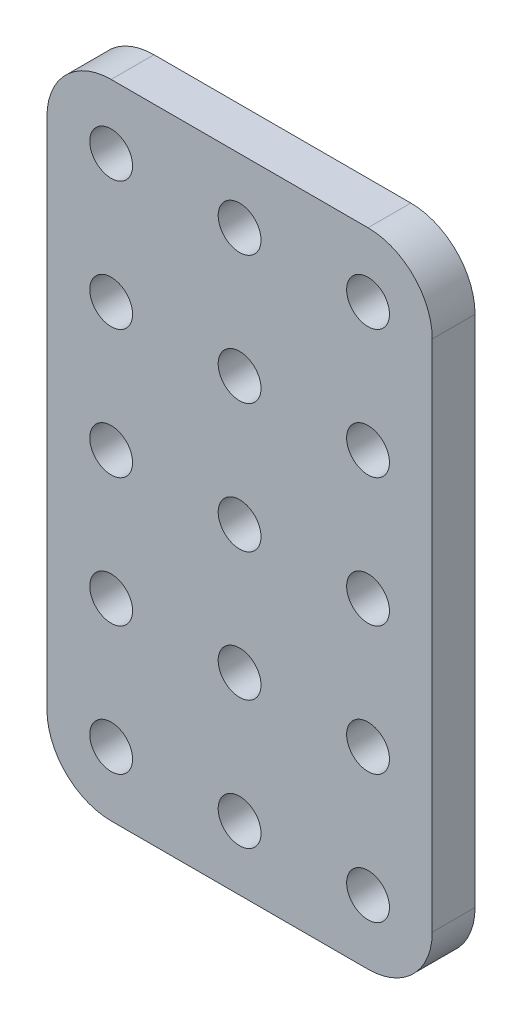
SolidWorks part; units mm, degrees
ref_plane "Alzado" through (0, 0, 0) normal (0, 0, 1) x (1, 0, 0)
ref_plane "Planta" through (0, 0, 0) normal (0, 1, 0) x (1, 0, 0)
ref_plane "Vista lateral" through (0, 0, 0) normal (1, 0, 0) x (0, 0, -1)
sketch "Model" plane through (0, 0, 0) normal (0, 0, 1) x (1, 0, 0)
  line L0 (-105.9434, 101.0565) -> (-105.9434, 65.0565)
  line L1 (-101.4434, 60.5565) -> (-83.4434, 60.5565)
  line L2 (-78.9434, 65.0565) -> (-78.9434, 101.0565)
  line L3 (-83.4434, 105.5565) -> (-101.4434, 105.5565)
  circle A0 centre (-101.4434, 101.0565) radius 1.5
  circle A1 centre (-92.4434, 101.0565) radius 1.5
  circle A2 centre (-83.4434, 101.0565) radius 1.5
  circle A3 centre (-101.4434, 92.0565) radius 1.5
  circle A4 centre (-92.4434, 92.0565) radius 1.5
  circle A5 centre (-83.4434, 92.0565) radius 1.5
  circle A6 centre (-101.4434, 83.0565) radius 1.5
  circle A7 centre (-92.4434, 83.0565) radius 1.5
  circle A8 centre (-83.4434, 83.0565) radius 1.5
  arc A9 (-101.4434, 105.5565) -> (-105.9434, 101.0565) centre (-101.4434, 101.0565) ccw
  arc A10 (-78.9434, 101.0565) -> (-83.4434, 105.5565) centre (-83.4434, 101.0565) ccw
  arc A11 (-105.9434, 65.0565) -> (-101.4434, 60.5565) centre (-101.4434, 65.0565) ccw
  arc A12 (-83.4434, 60.5565) -> (-78.9434, 65.0565) centre (-83.4434, 65.0565) ccw
  circle A13 centre (-101.4434, 74.0565) radius 1.5
  circle A14 centre (-92.4434, 74.0565) radius 1.5
  circle A15 centre (-83.4434, 74.0565) radius 1.5
  circle A16 centre (-101.4434, 65.0565) radius 1.5
  circle A17 centre (-92.4434, 65.0565) radius 1.5
  circle A18 centre (-83.4434, 65.0565) radius 1.5
extrude "Saliente-Extruir1" add sketch "Model" along normal blind 3
